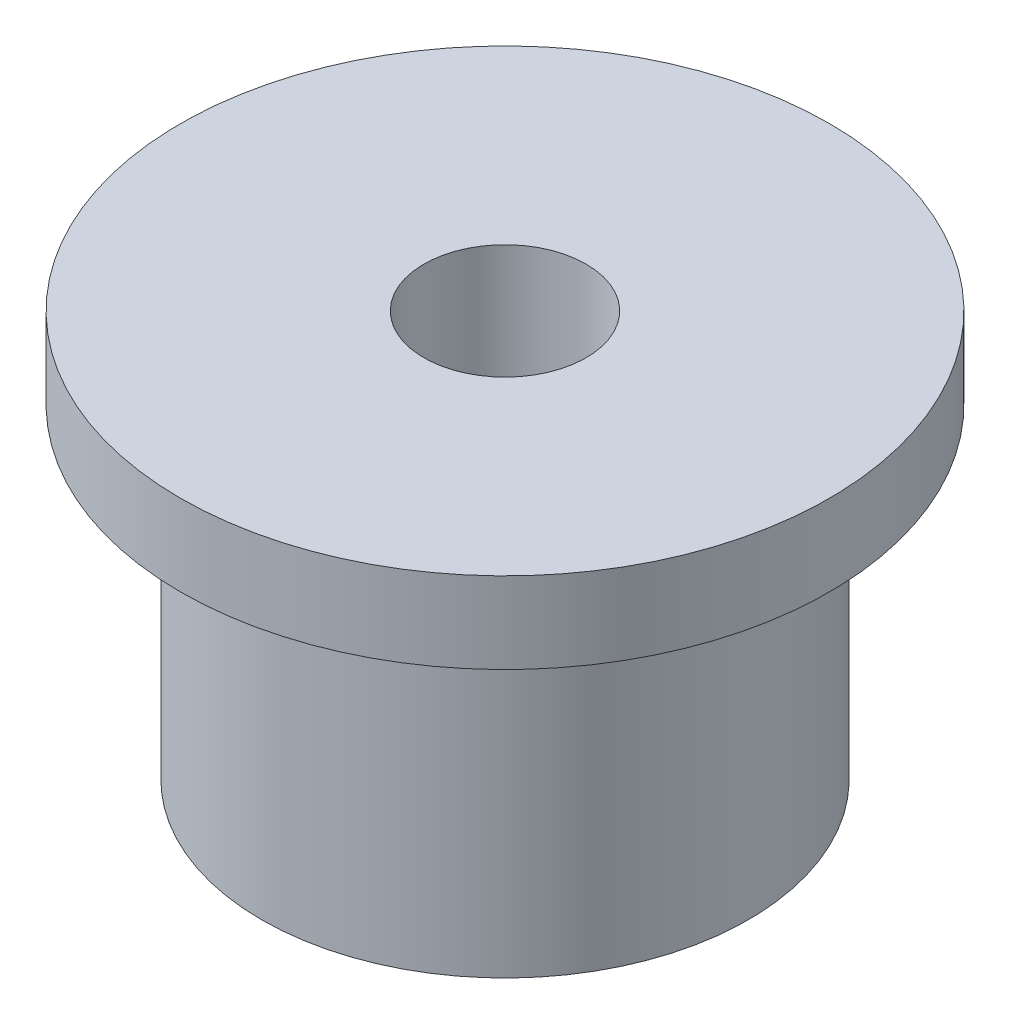
SolidWorks part; units mm, degrees
ref_plane "Front Plane" through (0, 0, 0) normal (0, 0, 1) x (1, 0, 0)
ref_plane "Top Plane" through (0, 0, 0) normal (0, 1, 0) x (1, 0, 0)
ref_plane "Right Plane" through (0, 0, 0) normal (1, 0, 0) x (0, 0, -1)
sketch "Sketch1" plane through (0, 0, 0) normal (0, 1, 0) x (1, 0, 0)
  circle A0 centre (0, 0) radius 100
  dimension "D1" = 200
extrude "Boss-Extrude1" add sketch "Sketch1" along normal blind 25
sketch "Sketch2" plane through (0, 0, 0) normal (0, -1, 0) x (1, 0, 0)
  circle A0 centre (0, 0) radius 75
  dimension "D1" = 150
extrude "Boss-Extrude2" add sketch "Sketch2" along normal blind 100
sketch "Sketch3" plane through (0, -100, 0) normal (0, -1, 0) x (1, 0, 0)
  circle A0 centre (0, 0) radius 25
  dimension "D1" = 50
extrude "Cut-Extrude1" cut sketch "Sketch3" against normal through all both
